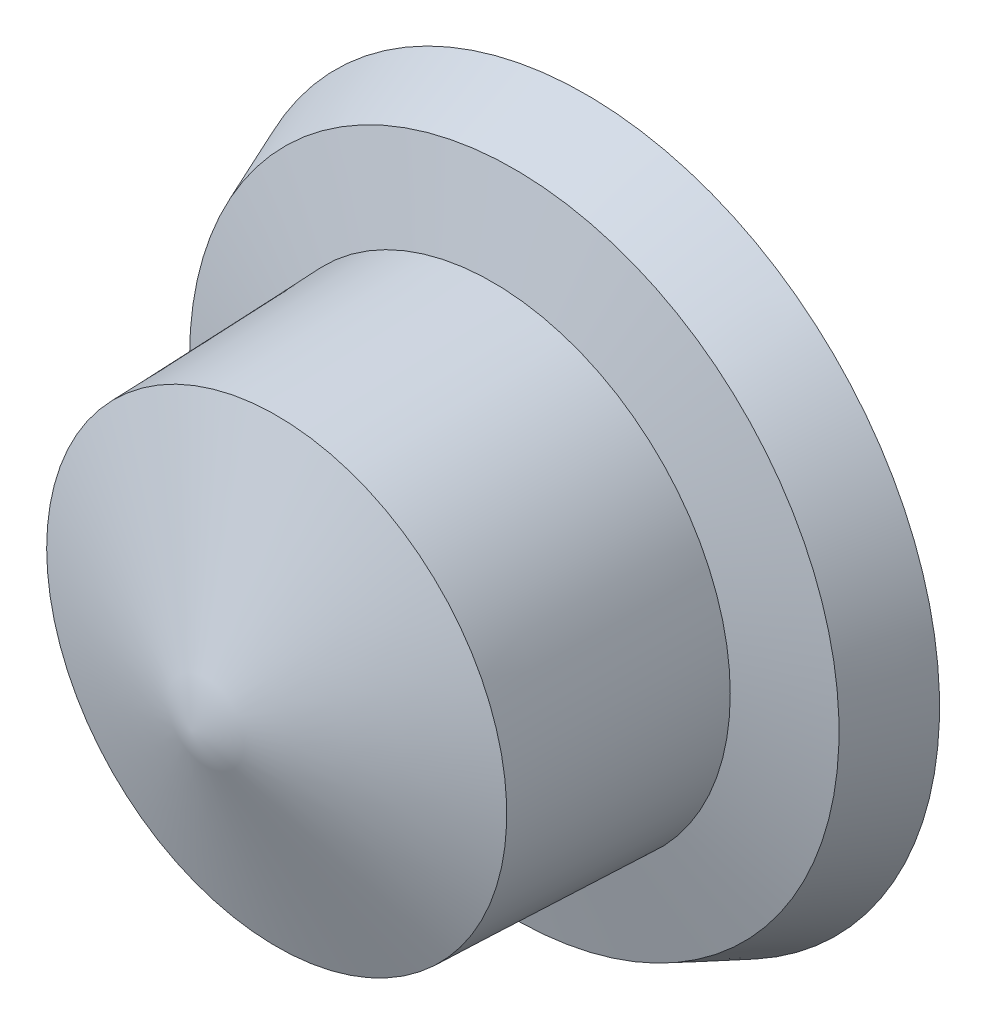
SolidWorks part; units mm, degrees
ref_plane "Front Plane" through (0, 0, 0) normal (0, 0, 1) x (1, 0, 0)
ref_plane "Top Plane" through (0, 0, 0) normal (0, 1, 0) x (1, 0, 0)
ref_plane "Right Plane" through (0, 0, 0) normal (1, 0, 0) x (0, 0, -1)
sketch "Sketch1" plane through (0, 0, 0) normal (1, 0, 0) x (0, 0, -1)
  line L0 (0, 0) -> (3.3332, 9.002)
  line L1 (3.3332, 9.002) -> (11.7782, 9.302)
  line L2 (11.7782, 9.302) -> (12.6299, 12.7071)
  line L3 (12.6299, 12.7071) -> (15.4282, 13.8417)
  line L4 (15.4282, 13.8417) -> (15.4282, 0)
  line L5 (15.4282, 0) -> (0, 0)
revolve "Revolve1" add sketch "Sketch1" angle 360 about L5
